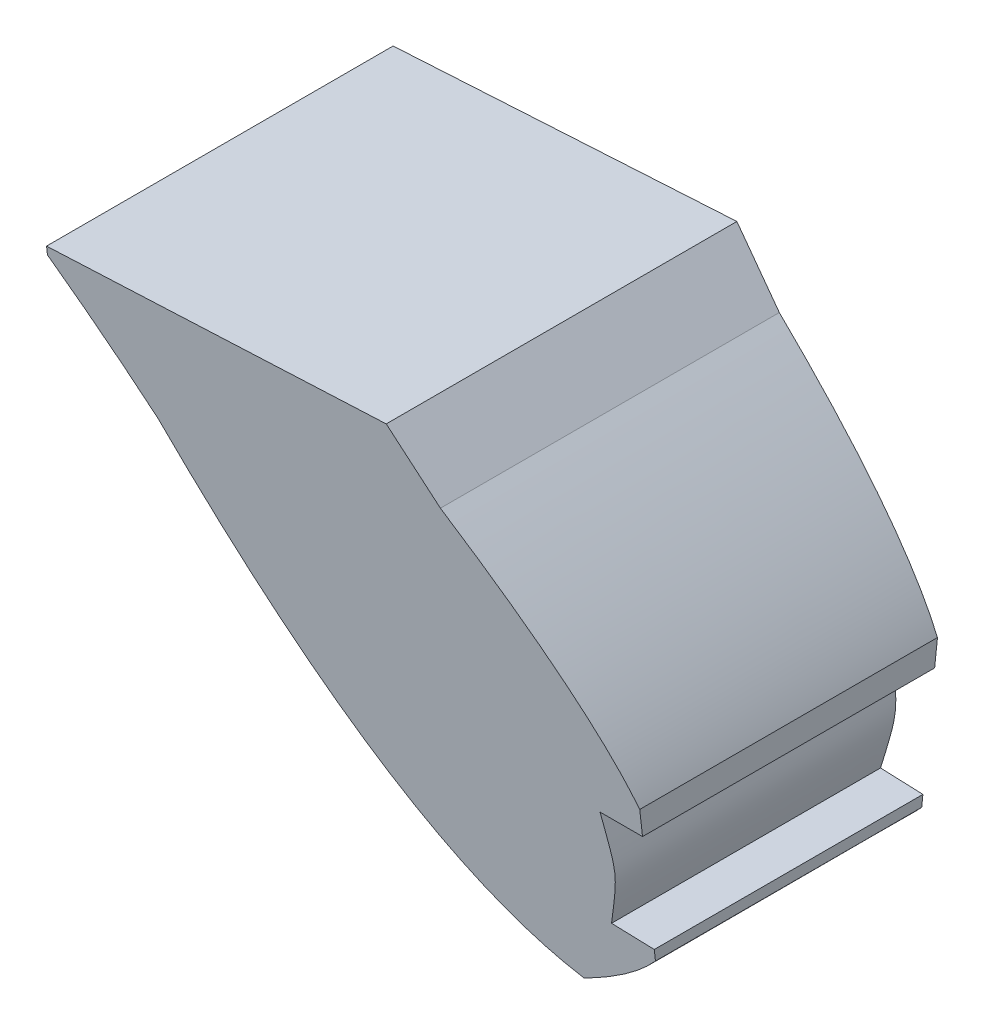
SolidWorks part; units mm, degrees
ref_plane "Alzado" through (0, 0, 0) normal (0, 0, 1) x (1, 0, 0)
ref_plane "Planta" through (0, 0, 0) normal (0, 1, 0) x (1, 0, 0)
ref_plane "Vista lateral" through (0, 0, 0) normal (1, 0, 0) x (0, 0, -1)
sketch "Croquis1" plane through (0, 0, 0) normal (0, 0, 1) x (1, 0, 0)
  line L0 (-8.9818, 12.6082) -> (-23.0359, 11.8716) construction
  line L1 (-8.9818, 12.6082) -> (-23.0359, 11.8716)
  line L2 (-8.9818, 12.6082) -> (-23.0359, 11.8716) construction
  line L4 (-8.9818, 12.6082) -> (-23.0359, 11.8716)
  line L6 (-1.3949, 1.9763) -> (0.3551, 2.2848) construction
  line L7 (-1.3949, 1.9763) -> (0.3551, 2.2848)
  line L8 (0.3551, 2.2848) -> (0.3551, 2.8423) construction
  line L9 (0.3551, 2.2848) -> (0.3551, 3.0015)
  line L10 (0.3551, -2.2848) -> (-1.3949, -2.2237) construction
  line L11 (0.3551, -2.2848) -> (-1.3949, -2.2237)
  line L12 (0.3551, 2.2848) -> (0.3551, -2.2848) construction
  line L13 (0.3551, -2.2848) -> (0.3551, -2.7233)
  line L14 (-8.9818, 12.6082) -> (-6.9949, 10.4774)
  line L15 (-23.0359, 11.5401) -> (-23.0359, 11.8716) construction
  line L16 (-23.0359, 11.5401) -> (-23.0359, 11.8716)
  arc A0 (-18.9452, 7.5409) -> (-23.0359, 11.5401) centre (-69.8841, -40.4718) ccw construction
  arc A1 (-18.9452, 7.5409) -> (-23.0359, 11.5401) centre (-69.8841, -40.4718) ccw
  spline S1 degree 2 poles (-828.7061, 3922.2202) (545.889, -3962.7836) (-262.0834, 3982.5902) knots 0.462185 0.462185 0.462185 0.537731 0.537731 0.537731 weights 1 1 1 only from (-18.9452, 7.5409) to (-2.8466, -5.0591) construction
  spline S2 degree 2 poles (-18.9452, 7.5409) (-10.215, -3.6976) (-2.8466, -5.0591) knots 0.497667 0.497667 0.497667 0.499554 0.499554 0.499554 weights 1 1 1
  spline S3 degree 2 poles (-3804.8689, 1232.5771) (3762.9122, -1369.6643) (-3716.5752, 1504.852) knots 0.462212 0.462212 0.462212 0.537836 0.537836 0.537836 weights 1 1 1 only from (0.3551, 3.0015) to (-6.9949, 10.4774) construction
  spline S4 degree 2 poles (0.3551, 3.0015) (-1.4487, 6.0584) (-6.9949, 10.4774) knots 0.500821 0.500821 0.500821 0.502013 0.502013 0.502013 weights 1 1 1
  spline S5 degree 2 poles (-1.3949, -2.2237) (-0.9075, -0.1237) (-1.3949, 1.9763) knots 0 0 0 1 1 1 weights 1 3.231801 1 construction
  spline S6 degree 2 poles (-1.3949, -2.2237) (-0.9075, -0.1237) (-1.3949, 1.9763) knots 0 0 0 1 1 1 weights 1 3.231801 1
  spline S7 degree 2 poles (-3997.263, 185.0077) (3984.2333, -348.7483) (-3965.0625, 511.2595) knots 0.462205 0.462205 0.462205 0.537778 0.537778 0.537778 weights 1 1 1 only from (-2.8466, -5.0591) to (0.3551, -2.7233) construction
  spline S8 degree 2 poles (-2.8466, -5.0591) (-0.7424, -3.9352) (0.3551, -2.7233) knots 0.498812 0.498812 0.498812 0.499413 0.499413 0.499413 weights 1 1 1
extrude "Saliente-Extruir1" add sketch "Croquis1" along normal mid plane 14.42 contours S2 S8 L13 L11 S6 L7 L9 S4 L14 L1 L16 A1
sketch "Croquis3" plane through (0, 0, 0) normal (0, 0, 1) x (1, 0, 0)
  line L0 (-6.742, 0) -> (0, 0) construction
  line L1 (-1.8181, 2) -> (-1.7771, 2.0103) construction
  line L3 (-1.8181, 2) -> (-0.1689, 2.4155) construction
  line L4 (-1.8181, 2) -> (0.3551, 3.0015)
  line L5 (0.3551, 3.0015) -> (0.3551, 0)
  line L6 (-1.9112, -2.1782) -> (0.3551, -2.2848)
  line L7 (0.3551, -2.2848) -> (0.3551, 0)
  parabola Q0 (-1.9112, -2.1782) -> (-1.8181, 2) focus (-3.3181, 0) apex (-1.3181, 0)
  dimension "D1" = 2
  dimension "D2" = 2
extrude "Cortar-Extruir1" [suppressed] cut sketch "Croquis3" against normal through all both and the other way through all
sketch "Croquis4" plane through (0, 0, 0) normal (0, 0, 1) x (1, 0, 0)
  line L0 (-1.3949, 1.9763) -> (0.3551, 2.2848) construction
  line L1 (-1.3949, 1.9763) -> (0.3551, 2.2848)
  line L2 (0.3551, 2.2848) -> (0.3551, 3.0015) construction
  line L3 (0.3551, 1.9763) -> (0.3551, 2.2848)
  line L4 (-1.3949, 1.9763) -> (0.3551, 1.9763)
  line L5 (0, 0) -> (-3.4665, 0) construction
  dimension "D1" = 0
extrude "Saliente-Extruir2" add sketch "Croquis4" along normal through all and the other way through all
sketch "Croquis7" plane through (0, 0, 0) normal (0, 0, 1) x (1, 0, 0)
  line L0 (0, 0) -> (-15.3945, 3.3171) construction
  line L1 (-17.3963, 18.9371) -> (-15.3945, 3.3171) construction
  line L2 (-15.3945, 3.3171) -> (-9.9316, -2.6296) construction
  line L3 (-15.3945, 3.3171) -> (-10.2385, 8.0535) construction
  line L4 (-17.3963, 18.9371) -> (-16.5429, 12.2783) construction
  line L5 (0, 0) -> (-1.3461, -2.2254) construction
  line L6 (-69.8841, 29.5282) -> (-81.9382, 42.5765) construction
  line L7 (-69.8841, 29.5282) -> (-20.9497, 29.5282) construction
  line L8 (-17.8101, 13.1658) -> (-25.5429, 13.1658)
  line L9 (-18.2059, 7.0951) -> (-21.9246, 11.9299) construction
  line L10 (0.3551, -2.5) -> (-2.4497, -2.0473)
  line L11 (-1.3461, -2.2254) -> (-2.0075, -3.6222) construction
  line L12 (-1.3461, -2.2254) -> (-1.4547, -2.8987) construction
  line L13 (-1.3461, -2.2254) -> (-1.2286, -1.4976) construction
  line L14 (0.3551, -2.2848) -> (0.3551, -2.7233) construction
  line L15 (0.3551, -2.2848) -> (-1.3949, -2.2237) construction
  line L16 (-2.0075, -3.6222) -> (-3.0629, -5.8512) construction
  line L17 (-2.6331, -4.9434) -> (-3.7044, -5.5324) construction
  line L18 (-2.6331, -4.9434) -> (-3.2248, -3.867) construction
  line L19 (-2.6331, -4.9434) -> (-2.2174, -6.1341) construction
  line L20 (-4.0838, -4.7637) -> (-1.6363, -5.0668) construction
  line L21 (-4.0838, -4.7637) -> (-0.036, -5.9454) construction
  line L22 (-4.0838, -4.7637) -> (-3.7621, -3.6616) construction
  line L23 (-4.0838, -4.7637) -> (-6.31, -3.7023) construction
  line L24 (-6.31, -3.7023) -> (-8.69, -2.5677) construction
  line L25 (-8.69, -2.5677) -> (-6.8421, -3.7725) construction
  line L26 (-8.69, -2.5677) -> (-7.9481, -1.4297) construction
  line L27 (-10.6884, -0.8477) -> (-8.69, -2.5677) construction
  line L28 (-10.6884, -0.8477) -> (-14.8546, 2.738) construction
  line L29 (-14.8546, 2.738) -> (-14.5337, 2.3989) construction
  line L30 (-14.8546, 2.738) -> (-14.6199, 2.9602) construction
  line L31 (-18.2059, 7.0951) -> (-14.8546, 2.738) construction
  line L32 (-8.9818, 12.6082) -> (-23.0359, 11.8716) construction
  line L33 (-8.9818, 12.6082) -> (-23.0359, 11.8716)
  line L34 (-21.9246, 11.9299) -> (-21.9826, 13.0367) construction
  line L35 (-21.9246, 11.9299) -> (-23.4156, 13.0367) construction
  arc A0 (-18.9452, 7.5409) -> (-23.0359, 11.5401) centre (-69.8841, -40.4718) ccw construction
  spline S0 degree 2 poles (-473.2528, 1954.0983) (272.8543, -1983.3606) (-71.9703, 1991.8157) knots 0.473236 0.473236 0.473236 0.526647 0.526647 0.526647 weights 1 1 1 only from (-18.9452, 7.5409) to (-2.8466, -5.0591) construction
  spline S1 degree 2 poles (-18.6263, 7.1332) (-10.0803, -3.7225) (-2.8466, -5.0591) knots 0.497702 0.497702 0.497702 0.499554 0.499554 0.499554 weights 1 1 1 construction
  spline S3 degree 2 poles (-2001.337, 58.5738) (1992.5148, -174.5103) (-1977.5574, 289.1588) knots 0.473271 0.473271 0.473271 0.526705 0.526705 0.526705 weights 1 1 1 only from (-2.8466, -5.0591) to (0.3551, -2.7233) construction
  spline S4 degree 2 poles (-2.8466, -5.0591) (-2.7385, -5.0013) (-2.6331, -4.9434) knots 0.498812 0.498812 0.498812 0.498843 0.498843 0.498843 weights 1 1 1
  dimension "D1" = 2.5
  dimension "D2" = 22
  dimension "D3" = 16.17
  dimension "D4" = 54.138
  dimension "D5" = 34.566
  dimension "D6" = 50.413
sketch "Croquis6" plane through (0, 0, 0) normal (1, 0, 0) x (0, 0, -1)
  line L0 (7.21, 12.6082) -> (7.21, 10.4774) construction
  line L1 (7.21, 12.6082) -> (7.21, -5.0591)
  line L2 (-7.21, 12.6082) -> (-7.21, 10.4774) construction
  line L3 (-7.21, 12.6082) -> (-7.21, -5.0591)
  line L4 (-7.21, -5.0591) -> (7.21, -5.0591) construction
  line L5 (-7.21, -5.0591) -> (-5.21, -5.0591)
  line L6 (7.21, 12.6082) -> (5.21, -5.0591)
  line L7 (-7.21, 12.6082) -> (-5.21, -5.0591)
  line L8 (5.21, -5.0591) -> (7.21, -5.0591)
  dimension "D1" = 2
  dimension "D2" = 2
extrude "Cortar-Extruir2" cut sketch "Croquis6" against normal through all and the other way through all
